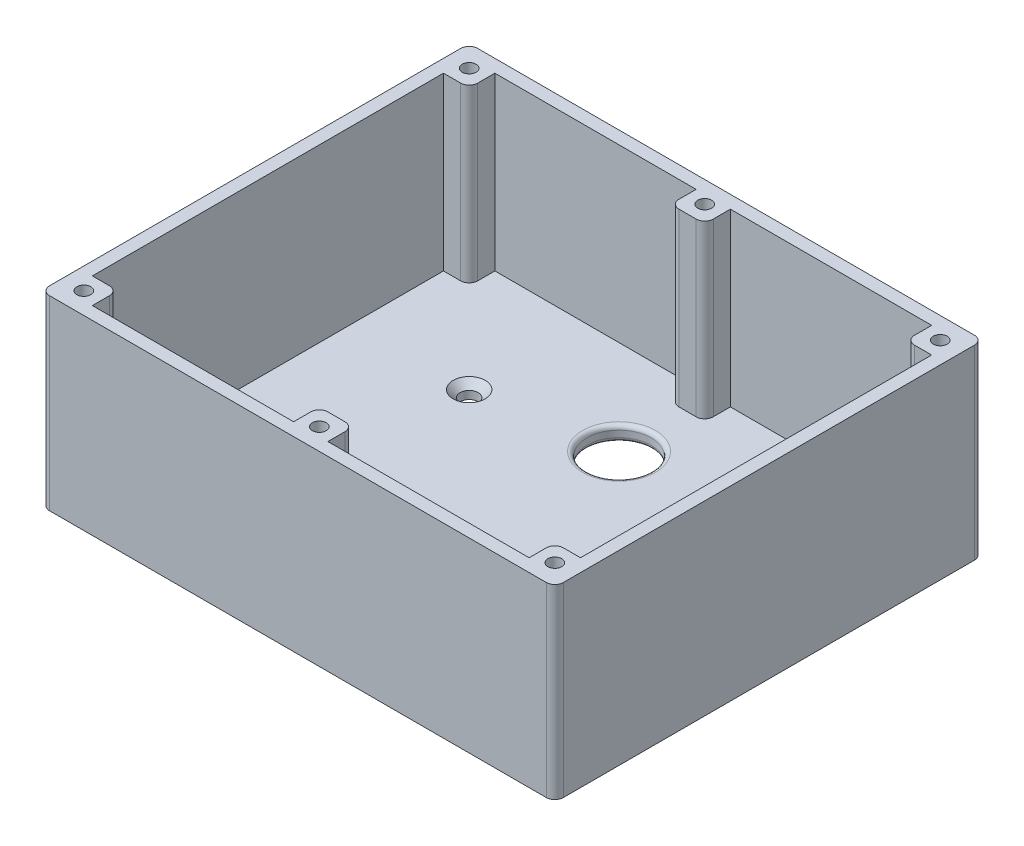
SolidWorks part; units mm, degrees
ref_plane "Front Plane" through (0, 0, 0) normal (0, 0, 1) x (1, 0, 0)
ref_plane "Top Plane" through (0, 0, 0) normal (0, 1, 0) x (1, 0, 0)
ref_plane "Right Plane" through (0, 0, 0) normal (1, 0, 0) x (0, 0, -1)
sketch "Sketch1" plane through (0, 0, 0) normal (0, 1, 0) x (1, 0, 0)
  line L1 (60, -50) -> (-60, -50)
  line L2 (60, -50) -> (60, 50)
  line L3 (60, 50) -> (-60, 50)
  line L4 (-60, -50) -> (-60, 50)
  line L5 (60, -50) -> (-60, 50) construction
  line L6 (60, 50) -> (-60, -50) construction
  point P0 (0, 0)
  dimension "D1" = 100
  dimension "D2" = 120
extrude "Bottom" add sketch "Sketch1" along normal blind 3.5
sketch "Sketch3" plane through (0, 3.5, 0) normal (0, 1, 0) x (1, 0, 0)
  line L0 (-60, 50) -> (60, 50)
  line L1 (60, 50) -> (60, -50)
  line L2 (60, -50) -> (-60, -50)
  line L3 (-60, -50) -> (-60, 50)
  line L4 (-51, 47) -> (-4, 47)
  line L5 (57, 41) -> (57, -41)
  line L6 (51, -47) -> (4, -47)
  line L7 (0, 50) -> (0, -50) construction
  line L8 (-57, 41) -> (-51, 41)
  line L9 (-51, 41) -> (-51, 47)
  line L10 (51, 47) -> (51, 41)
  line L11 (51, 41) -> (57, 41)
  line L12 (57, -41) -> (51, -41)
  line L13 (51, -41) -> (51, -47)
  line L14 (-57, -41) -> (-51, -41)
  line L15 (-51, -41) -> (-51, -47)
  line L16 (-57, -41) -> (-57, 41)
  line L17 (0, 0) -> (57, 0) construction
  line L18 (4, -47) -> (4, -41)
  line L19 (-4, 47) -> (-4, 41)
  line L20 (-4, 41) -> (4, 41)
  line L21 (4, 47) -> (4, 41)
  line L22 (0, 41) -> (0, 42.7097) construction
  line L23 (4, 47) -> (51, 47)
  line L24 (-4, -41) -> (4, -41)
  line L25 (-4, -47) -> (-4, -41)
  line L26 (-4, -47) -> (-51, -47)
  dimension "D1" = 3
  dimension "D2" = 3
  dimension "D3" = 3
  dimension "D4" = 3
  dimension "D5" = 6
  dimension "D6" = 8
extrude "Wall" add sketch "Sketch3" along normal blind 40
sketch "Sketch4" plane through (0, 43.5, 0) normal (0, 1, 0) x (1, 0, 0)
  line L0 (-60, 50) -> (-60, -50) construction
  line L1 (60, 50) -> (-60, 50) construction
  line L2 (60, -50) -> (60, 50) construction
  line L3 (-60, -50) -> (60, -50) construction
  line L4 (0, 50) -> (0, 30.3541) construction
  line L5 (60, 0) -> (33.8613, 0) construction
  circle A0 centre (-55, 45) radius 1.625
  circle A1 centre (55, 45) radius 1.625
  circle A2 centre (55, -45) radius 1.625
  circle A3 centre (-55, -45) radius 1.625
  circle A4 centre (0, 45) radius 1.625
  circle A5 centre (0, -45) radius 1.625
  dimension "D1" = 3.25
  dimension "D4" = 5
  dimension "D2" = 5
  dimension "D3" = 5
  dimension "D5" = 5
extrude "Top Plate Screw Holes" cut sketch "Sketch4" against normal blind 30 draft 1
fillet "Fillet14" radius 2 1 edges at (-4, 23.5, 41)
fillet "Fillet13" radius 2 1 edges at (4, 23.5, 41)
fillet "Fillet12" radius 2 1 edges at (-4, 23.5, -41)
fillet "Fillet11" radius 2 1 edges at (4, 23.5, -41)
fillet "Fillet1" radius 2 1 edges at (-51, 23.5, 41)
fillet "Fillet2" radius 2 1 edges at (51, 23.5, 41)
fillet "Fillet3" radius 2 1 edges at (51, 23.5, -41)
fillet "Fillet4" radius 2 1 edges at (-51, 23.5, -41)
fillet "Fillet5" radius 2 1 edges at (-60, 21.75, -50)
fillet "Fillet6" radius 2 1 edges at (60, 21.75, -50)
fillet "Fillet7" radius 2 1 edges at (60, 21.75, 50)
fillet "Fillet8" radius 2 1 edges at (-60, 21.75, 50)
sketch "M4 Mount" plane through (0, 3.5, 0) normal (0, -1, 0) x (1, 0, 0)
  line L0 (60, 48) -> (60, -48) construction
  line L1 (0, 0) -> (23.8675, 0) construction
  line L2 (0, 0) -> (0, -19.9393) construction
  circle A0 centre (30, -20) radius 2.1
  circle A1 centre (30, 20) radius 2.1
  circle A2 centre (-30, 20) radius 2.1
  circle A3 centre (-30, -20) radius 2.1
  dimension "D1" = 4.2
  dimension "D2" = 30
  dimension "D3" = 20
  dimension "D4" = 20
extrude "M4 Mount Cut" cut sketch "M4 Mount" along normal through all
sketch "M4 Screw Heads" plane through (0, 3.5, 0) normal (0, 1, 0) x (1, 0, 0)
  circle A0 centre (30, -20) radius 3.75
  circle A1 centre (30, 20) radius 3.75
  circle A2 centre (-30, 20) radius 3.75
  circle A3 centre (-30, -20) radius 3.75
  dimension "D1" = 7.5
extrude "Cut-Extrude3" cut sketch "M4 Screw Heads" against normal blind 10 draft 45
sketch "Sketch7" plane through (0, 0, 0) normal (0, -1, 0) x (1, 0, 0)
  line L0 (58, -50) -> (-58, -50) construction
  line L1 (60, 48) -> (60, -48) construction
  circle A0 centre (0, -25) radius 7.5
  point P2 (0, -50)
  dimension "D1" = 15
  dimension "D2" = 25
  dimension "D3" = 60
extrude "USB Cabel Cut" cut sketch "Sketch7" against normal through all
fillet "Fillet9" radius 1 1 edges at (0, 0, -32.5)
fillet "Fillet10" radius 1 1 edges at (0, 3.5, -17.5)
equation "\"BOXWALL\"=3"
equation "\"D1@Sketch3\"=\"BOXWALL\""
equation "\"D2@Sketch3\"=\"BOXWALL\""
equation "\"D3@Sketch3\"=\"BOXWALL\""
equation "\"D4@Sketch3\"=\"BOXWALL\""
